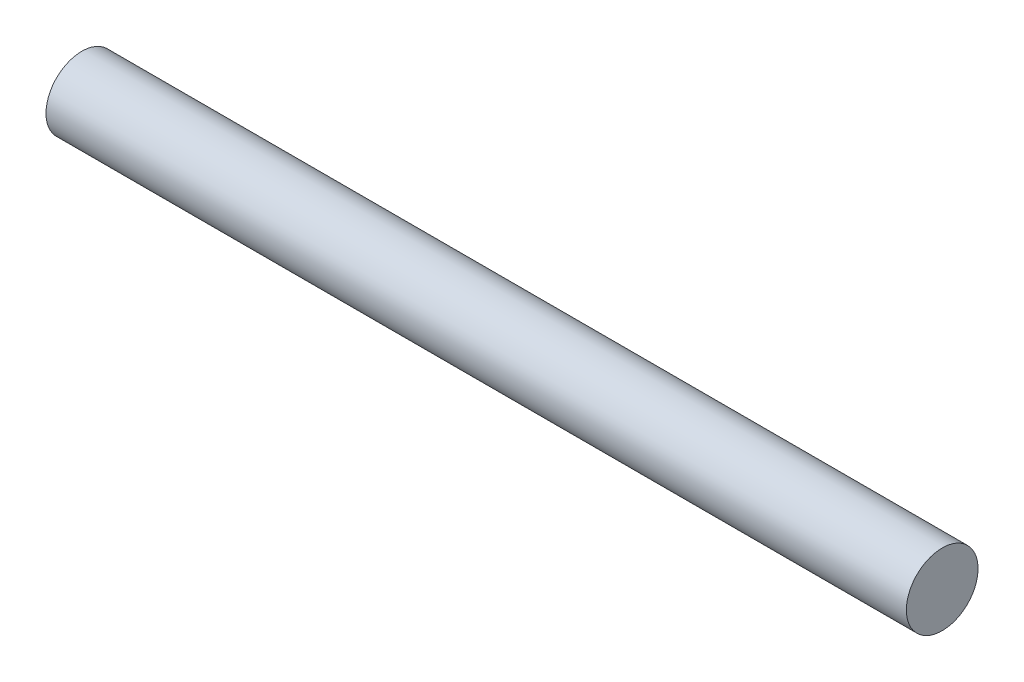
SolidWorks part; units mm, degrees
ref_plane "Front Plane" through (0, 0, 0) normal (0, 0, 1) x (1, 0, 0)
ref_plane "Top Plane" through (0, 0, 0) normal (0, 1, 0) x (1, 0, 0)
ref_plane "Right Plane" through (0, 0, 0) normal (1, 0, 0) x (0, 0, -1)
sketch "Sketch1" plane through (0, 0, 0) normal (1, 0, 0) x (0, 0, -1)
  circle A0 centre (0, 0) radius 6.35
  dimension "D1" = 12.7
extrude "Boss-Extrude1" add sketch "Sketch1" along normal blind 152.4
